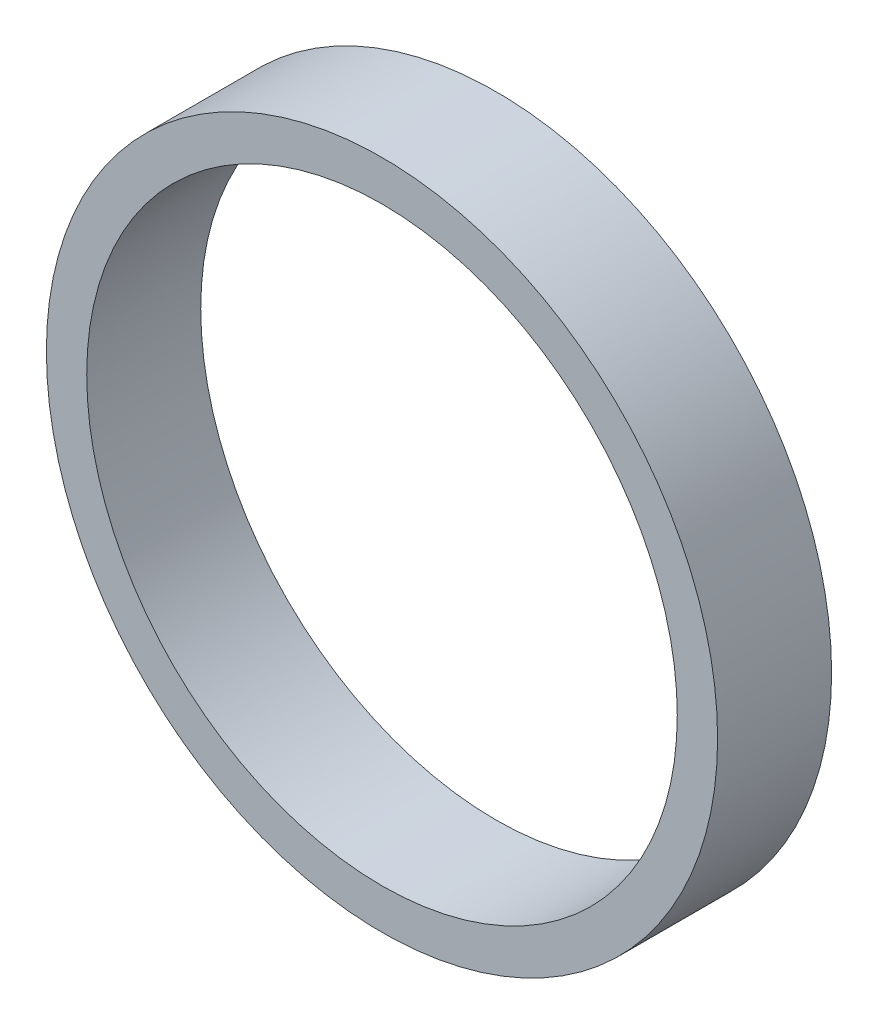
SolidWorks part; units mm, degrees
ref_plane "Front Plane" through (0, 0, 0) normal (0, 0, 1) x (1, 0, 0)
ref_plane "Top Plane" through (0, 0, 0) normal (0, 1, 0) x (1, 0, 0)
ref_plane "Right Plane" through (0, 0, 0) normal (1, 0, 0) x (0, 0, -1)
sketch "Sketch9" plane through (0, 0, 0) normal (0, 1, 0) x (1, 0, 0)
  line L0 (2.9258, 0.4969) -> (2.5742, 0.4969)
  line L1 (2.5742, 0.4969) -> (2.5742, -0.4969)
  line L2 (2.5742, -0.4969) -> (2.9258, -0.4969)
  line L3 (2.9258, -0.4969) -> (2.9258, 0.4969)
  line L4 (0, 0.4969) -> (0, -0.4969) construction
  point P6 (0, 0)
  dimension "D1" = 2.5742
  dimension "D2" = 2.9258
  dimension "D3" = 0.9939
revolve "Revolve5" add sketch "Sketch9" angle 360 about L4
